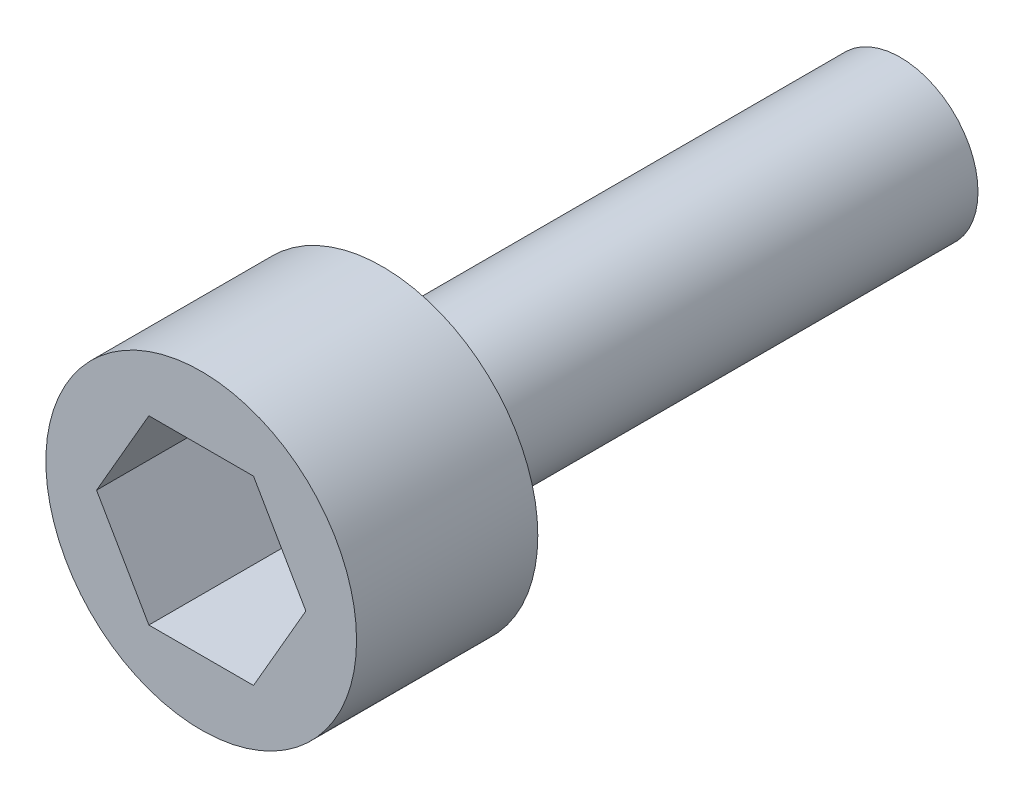
SolidWorks part; units mm, degrees
ref_plane "Front Plane" through (0, 0, 0) normal (0, 0, 1) x (1, 0, 0)
ref_plane "Top Plane" through (0, 0, 0) normal (0, 1, 0) x (1, 0, 0)
ref_plane "Right Plane" through (0, 0, 0) normal (1, 0, 0) x (0, 0, -1)
sketch "Sketch1" plane through (0, 0, 0) normal (0, 0, 1) x (1, 0, 0)
  circle A0 centre (0, 0) radius 3
  dimension "D1" = 6
extrude "Head Boss-Extrude1" add sketch "Sketch1" along normal blind 3.5
sketch "Sketch3" plane through (0, 0, 3.5) normal (0, 0, 1) x (1, 0, 0)
  line L0 (-1.0104, 1.75) -> (1.0104, 1.75)
  line L1 (1.0104, 1.75) -> (2.0207, 0)
  line L2 (2.0207, 0) -> (1.0104, -1.75)
  line L3 (1.0104, -1.75) -> (-1.0104, -1.75)
  line L4 (-1.0104, -1.75) -> (-2.0207, 0)
  line L5 (-2.0207, 0) -> (-1.0104, 1.75)
  line L6 (-2.0207, 0) -> (0, 0) construction
  line L7 (2.0207, 0) -> (0, 0) construction
  line L8 (-1.0104, -1.75) -> (0, 0) construction
  line L9 (0, 0) -> (1.0104, 1.75) construction
  line L10 (-1.0104, 1.75) -> (0, 0) construction
  line L11 (0, 0) -> (1.0104, -1.75) construction
  dimension "D1" = 60
  dimension "D2" = 60
  dimension "D3" = 60
  dimension "D4" = 60
  dimension "D5" = 60
  dimension "D6" = 3.5
extrude "Head Hex Cut-Extrude1" cut sketch "Sketch3" against normal blind 2.8
sketch "Sketch2" plane through (0, 0, 0) normal (0, 0, 1) x (1, 0, 0)
  circle A0 centre (0, 0) radius 1.5
  dimension "D1" = 3
extrude "Screw Boss-Extrude2" add sketch "Sketch2" against normal blind 10
